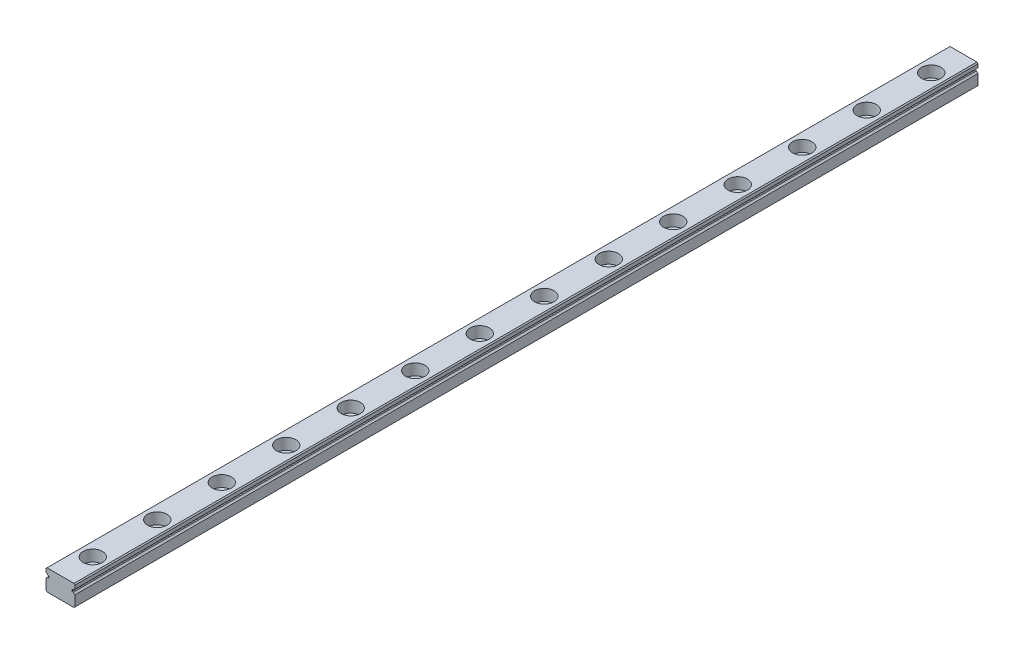
SolidWorks part; units mm, degrees
material "AISI 304"
ref_plane "前视基准面" through (0, 0, 0) normal (0, 0, 1) x (1, 0, 0)
ref_plane "上视基准面" through (0, 0, 0) normal (0, 1, 0) x (1, 0, 0)
ref_plane "右视基准面" through (0, 0, 0) normal (1, 0, 0) x (0, 0, -1)
other "Configuration Table"
sketch "草图2" plane through (0, 0, 0) normal (0, 0, 1) x (1, 0, 0)
  line L16 (4.1775, 6.5) -> (-4.1775, 6.5)
  line L17 (4.5, 6.1775) -> (4.1775, 6.5)
  line L18 (4.5, 5.1038) -> (4.5, 6.1775)
  line L19 (3.9862, 4.62) -> (3.6262, 4.62)
  line L20 (3.5362, 4.53) -> (3.5362, 4.17)
  line L21 (3.9862, 4.08) -> (3.6262, 4.08)
  line L22 (4.5, 0.3225) -> (4.5, 3.5963)
  line L23 (4.1775, 0) -> (4.5, 0.3225)
  line L24 (-4.1775, 0) -> (4.1775, 0)
  line L25 (-4.1775, 0) -> (-4.5, 0.3225)
  line L26 (-4.5, 0.3225) -> (-4.5, 3.5963)
  line L27 (-3.9862, 4.08) -> (-3.6262, 4.08)
  line L28 (-3.5362, 4.53) -> (-3.5362, 4.17)
  line L29 (-3.9862, 4.62) -> (-3.6262, 4.62)
  line L30 (-4.5, 5.1038) -> (-4.5, 6.1775)
  line L31 (-4.5, 6.1775) -> (-4.1775, 6.5)
  arc A8 (4.5, 5.1038) -> (3.9862, 4.62) centre (4.725, 4.35) ccw
  arc A9 (3.6262, 4.62) -> (3.5362, 4.53) centre (3.6262, 4.53) ccw
  arc A10 (3.5362, 4.17) -> (3.6262, 4.08) centre (3.6262, 4.17) ccw
  arc A11 (3.9862, 4.08) -> (4.5, 3.5963) centre (4.725, 4.35) ccw
  arc A12 (-4.5, 3.5963) -> (-3.9862, 4.08) centre (-4.725, 4.35) ccw
  arc A13 (-3.6262, 4.08) -> (-3.5362, 4.17) centre (-3.6262, 4.17) ccw
  arc A14 (-3.5362, 4.53) -> (-3.6262, 4.62) centre (-3.6262, 4.53) ccw
  arc A15 (-3.9862, 4.62) -> (-4.5, 5.1038) centre (-4.725, 4.35) ccw
  dimension "D9" = 0.7866
  dimension "D10" = 0.09
  dimension "D11" = 0.3225
  dimension "D12" = 0.5138
  dimension "D13" = 0.9638
  dimension "D14" = 8.0362
  dimension "D15" = 3.5963
  dimension "D16" = 6.1775
extrude "凸台-拉伸1" add sketch "草图2" against normal blind 280
sketch "草图3" plane through (0, 0, 0) normal (1, 0, 0) x (0, 0, -1)
  line L7 (7, 6.5) -> (7, 3)
  line L8 (7, 3) -> (8.25, 3)
  line L9 (8.25, 3) -> (8.25, 0)
  line L10 (7, 6.5) -> (10, 6.5)
  line L11 (10, 6.5) -> (10, 0)
  line L12 (10, 0) -> (8.25, 0)
  line L13 (280, 0) -> (0, 0) construction
  dimension "D1" = 1.75
  dimension "D2" = 3
  dimension "D3" = 6.5
  dimension "D4" = 10
revolve "切除-旋转1" cut sketch "草图3" angle 360 about L11
pattern_linear "阵列(线性)1" count 14 spacing 20 along (0, 0, -1) of "切除-旋转1"
equation "\"D\"= 10'端孔距[3,17]"
equation "\"L\"= 280'总长"
equation "\"D1@凸台-拉伸1\"=\"L\""
equation "\"H\"= 20'孔距（勿动）"
equation "\"D1@阵列(线性)1\"= int ( \"L\" / \"H\" )'孔数"
equation "\"D4@草图3\"=\"D\""
equation "\"D3@阵列(线性)1\"=\"H\""
